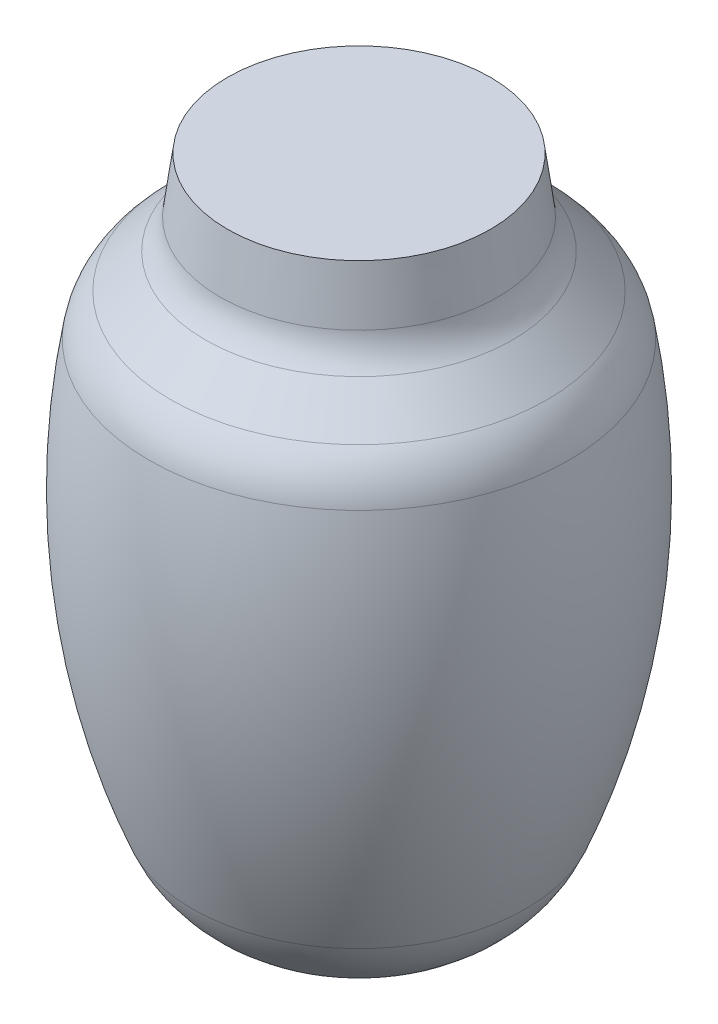
SolidWorks part; units mm, degrees
ref_plane "Front Plane" through (0, 0, 0) normal (0, 0, 1) x (1, 0, 0)
ref_plane "Top Plane" through (0, 0, 0) normal (0, 1, 0) x (1, 0, 0)
ref_plane "Right Plane" through (0, 0, 0) normal (1, 0, 0) x (0, 0, -1)
sketch "Sketch3" plane through (0, 0, 0) normal (0, 0, 1) x (1, 0, 0)
  line L1 (527.8458, 345.2208) -> (519.3827, 353.684)
  line L2 (515.7761, 360.9723) -> (513.9637, 374.4562)
  line L3 (513.9637, 374.4562) -> (481.7195, 374.4562)
  line L5 (481.7195, 374.4562) -> (481.7195, 214.6445) construction
  line L6 (481.7195, 374.4562) -> (481.7195, 214.6445)
  line L8 (493.1619, 214.6445) -> (481.7195, 214.6445)
  arc A0 (533.1426, 335.0209) -> (527.8458, 345.2208) centre (514.3754, 331.7504) ccw
  arc A1 (519.3827, 353.684) -> (515.7761, 360.9723) centre (528.3629, 362.6642) cw
  arc A2 (493.1619, 214.6445) -> (522.6349, 234.5876) centre (493.1619, 246.3945) ccw
  arc A6 (533.1426, 335.0209) -> (522.6349, 234.5876) centre (351.114, 303.299) cw
  dimension "D1" = 19.05
  dimension "D2" = 12.7
  dimension "D3" = 31.75
revolve "Revolve2" add sketch "Sketch3" angle 360 about L5
